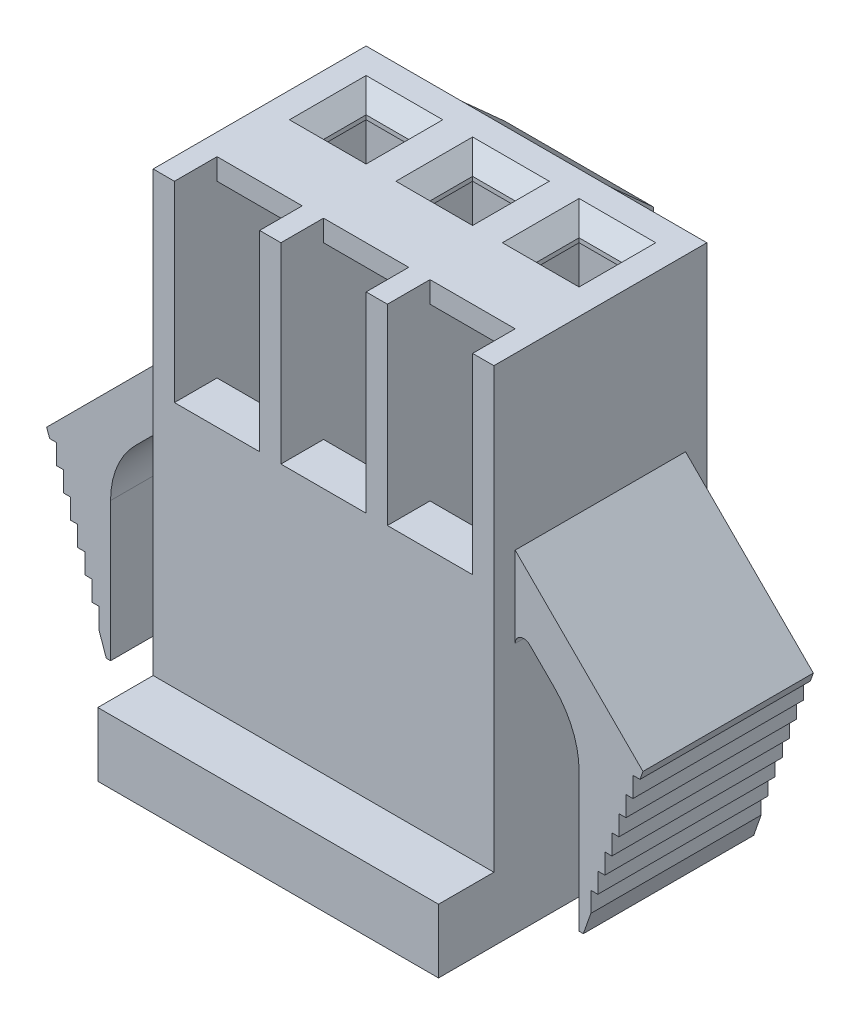
SolidWorks part; units mm, degrees
material "ABS"
ref_plane "Ebene vorne" through (0, 0, 0) normal (0, 0, 1) x (1, 0, 0)
ref_plane "Ebene oben" through (0, 0, 0) normal (0, 1, 0) x (1, 0, 0)
ref_plane "Ebene rechts" through (0, 0, 0) normal (1, 0, 0) x (0, 0, -1)
sketch "Skizze1" plane through (0, 0, 0) normal (0, 0, 1) x (1, 0, 0)
  line L1 (-4, 0) -> (4, 0)
  line L2 (-4, 0) -> (-4, 11.8)
  line L3 (-4, 11.8) -> (4, 11.8)
  line L4 (4, 0) -> (4, 11.8)
  point P4 (0, 0)
  dimension "D1" = 8
  dimension "D2" = 11.8
extrude "Aufsatz-Linear austragen1" add sketch "Skizze1" along normal mid plane 5
sketch "Skizze2" plane through (0, 0, 2.5) normal (0, 0, 1) x (1, 0, 0)
  line L0 (4, 0) -> (4, 11.8) construction
  line L1 (-4, 0) -> (4, 0)
  line L2 (-4, 0) -> (-4, 1.5)
  line L3 (-4, 1.5) -> (4, 1.5)
  line L4 (4, 0) -> (4, 1.5)
  dimension "D1" = 1.5
extrude "Aufsatz-Linear austragen2" add sketch "Skizze2" along normal blind 1.3
sketch "Skizze3" plane through (0, 0, -2.5) normal (0, 0, -1) x (-1, 0, 0)
  line L0 (0, 0) -> (0, 11.8) construction
  line L1 (-4, 0) -> (-1.8, 0)
  line L2 (-4, 0) -> (-4, 1.5)
  line L3 (-4, 1.5) -> (-1.8, 1.5)
  line L4 (-1.8, 0) -> (-1.8, 1.5)
  line L5 (-4, 11.8) -> (4, 11.8) construction
  line L6 (1.8, 0) -> (1.8, 1.5)
  line L7 (4, 1.5) -> (1.8, 1.5)
  line L8 (4, 0) -> (4, 1.5)
  line L9 (4, 0) -> (1.8, 0)
  dimension "D1" = 2.2
  dimension "D2" = 1.5
extrude "Aufsatz-Linear austragen3" add sketch "Skizze3" along normal blind 1.2
sketch "Skizze4" plane through (0, 0, 0) normal (1, 0, 0) x (0, 0, -1)
  line L0 (2.5, 11.8) -> (3.5, 10.9)
  line L1 (3.5, 10.9) -> (3.5, 10.4)
  line L2 (3.5, 10.4) -> (2.5, 10.4)
  line L3 (2.5, 1.5) -> (2.5, 11.8) construction
  line L4 (2.5, 10.4) -> (2.5, 11.8)
  dimension "D1" = 1.4
  dimension "D2" = 0.5
  dimension "D3" = 1
extrude "Aufsatz-Linear austragen4" add sketch "Skizze4" along normal mid plane 3.5
sketch "Skizze5" plane through (0, 0, -2.5) normal (0, 0, -1) x (-1, 0, 0)
  line L0 (2.9, 1.5) -> (2.9, 2.8) construction
  line L1 (4, 1.5) -> (1.8, 1.5) construction
  line L2 (1.8, 1.5) -> (2.9, 2.8)
  line L3 (2.9, 2.8) -> (4, 1.5)
  line L4 (4, 1.5) -> (1.8, 1.5)
  dimension "D1" = 1.3
extrude "Aufsatz-Linear austragen5" add sketch "Skizze5" along normal blind 0.05
sketch "Skizze6" plane through (0, 0, 0) normal (0, -1, 0) x (1, 0, 0)
  line L0 (-4, 3.8) -> (-4, -3.7) construction
  line L1 (-3.5, 1.5) -> (-1.5, 1.5)
  line L2 (-3.5, 1.5) -> (-3.5, -2)
  line L3 (-3.5, -2) -> (-1.5, -2)
  line L4 (-1.5, 1.5) -> (-1.5, -2)
  line L5 (-1.8, -2.5) -> (1.8, -2.5) construction
  dimension "D1" = 2
  dimension "D2" = 0.5
  dimension "D3" = 3.5
  dimension "D4" = 0.5
extrude "Schnitt-Linear austragen1" cut sketch "Skizze6" against normal offset from surface (11.3 mm away) 0.5 up to face at (0, 11.8, -0.8333)
sketch "Skizze7" plane through (0, 0, 2.5) normal (0, 0, 1) x (1, 0, 0)
  line L0 (-3.5, 11.3) -> (-3.5, 0) construction
  line L1 (-3.5, 11.8) -> (-1.5, 11.8)
  line L2 (-3.5, 11.8) -> (-3.5, 7.3)
  line L3 (-3.5, 7.3) -> (-1.5, 7.3)
  line L4 (-1.5, 11.8) -> (-1.5, 7.3)
  line L5 (-1.5, 11.3) -> (-1.5, 0) construction
  line L7 (4, 11.8) -> (-4, 11.8) construction
  dimension "D1" = 4.5
extrude "Schnitt-Linear austragen2" cut sketch "Skizze7" against normal up to surface (1 mm away) up to face at (-2.5, 5.65, 1.5)
sketch "Skizze8" plane through (0, 11.3, 0) normal (0, -1, 0) x (1, 0, 0)
  line L0 (-2.5, -2) -> (-2.5, 1.5) construction
  line L1 (-3, -0.5) -> (-2, -0.5)
  line L2 (-3, -0.5) -> (-3, -1.5)
  line L3 (-3, -1.5) -> (-2, -1.5)
  line L4 (-2, -0.5) -> (-2, -1.5)
  line L5 (-1.5, -2) -> (-3.5, -2) construction
  line L6 (-1.5, 1.5) -> (-3.5, 1.5) construction
  dimension "D1" = 1
  dimension "D2" = 1
  dimension "D3" = 0.5
extrude "Schnitt-Linear austragen3" cut sketch "Skizze8" against normal through all
chamfer "Fase1" distance 0.4 angle 45 4 edges at (-2.5, 11.8, -1.5) (-2, 11.8, -1) (-2.5, 11.8, -0.5) (-3, 11.8, -1)
pattern_linear "Lineares Muster1" count 3 spacing 2.5 along (1, 0, 0) of "Schnitt-Linear austragen1", "Schnitt-Linear austragen2", "Schnitt-Linear austragen3", "Fase1"
sketch "Skizze9" plane through (0, 0, 0) normal (0, 0, 1) x (1, 0, 0)
  line L0 (-4, 7.8) -> (-7, 4.8)
  line L1 (-4, 11.8) -> (-4, 1.5) construction
  line L2 (-7, 4.8) -> (-5.6, 0.8)
  line L3 (-5.6, 0.8) -> (-5.5, 0.8)
  line L4 (-5.5, 0.8) -> (-5.5, 4.8858)
  line L5 (-5.5, 4.8858) -> (-4, 6.3858)
  line L6 (-4, 6.3858) -> (-4, 7.8)
  line L7 (-3.5, 11.8) -> (-4, 11.8) construction
  dimension "D1" = 3
  dimension "D2" = 1
  dimension "D3" = 4
  dimension "D4" = 45
  dimension "D5" = 0.1
  dimension "D6" = 1.5
  dimension "D7" = 7
extrude "Aufsatz-Linear austragen6" add sketch "Skizze9" along normal mid plane 4
sketch "Skizze11" plane through (0, 0, 0) normal (0, 0, 1) x (1, 0, 0)
  line L0 (-5.9402, 1.7719) -> (-5.775, 1.7719)
  line L1 (-7, 4.8) -> (-5.6, 0.8) construction
  line L2 (-5.775, 1.7719) -> (-5.775, 1.3)
  line L3 (-5.775, 1.3) -> (-5.9402, 1.7719)
  line L4 (-5.6, 0.8) -> (-5.5, 0.8) construction
  dimension "D1" = 0.5
  dimension "D2" = 0.5
extrude "Schnitt-Linear austragen4" cut sketch "Skizze11" along normal mid plane 5
pattern_linear "Lineares Muster2" count 7 spacing 0.5 along (-0.3304, 0.9439, 0) of "Schnitt-Linear austragen4"
fillet "Verrundung1" radius 2 1 edges at (-5.5, 4.8858, 0)
fillet "Verrundung2" radius 0.2 1 edges at (-4, 6.3858, 0)
mirror "Spiegeln1" about plane through (0, 0, 0) normal (1, 0, 0) of "Lineares Muster2", "Schnitt-Linear austragen4", "Verrundung2", "Aufsatz-Linear austragen6", "Verrundung1"
